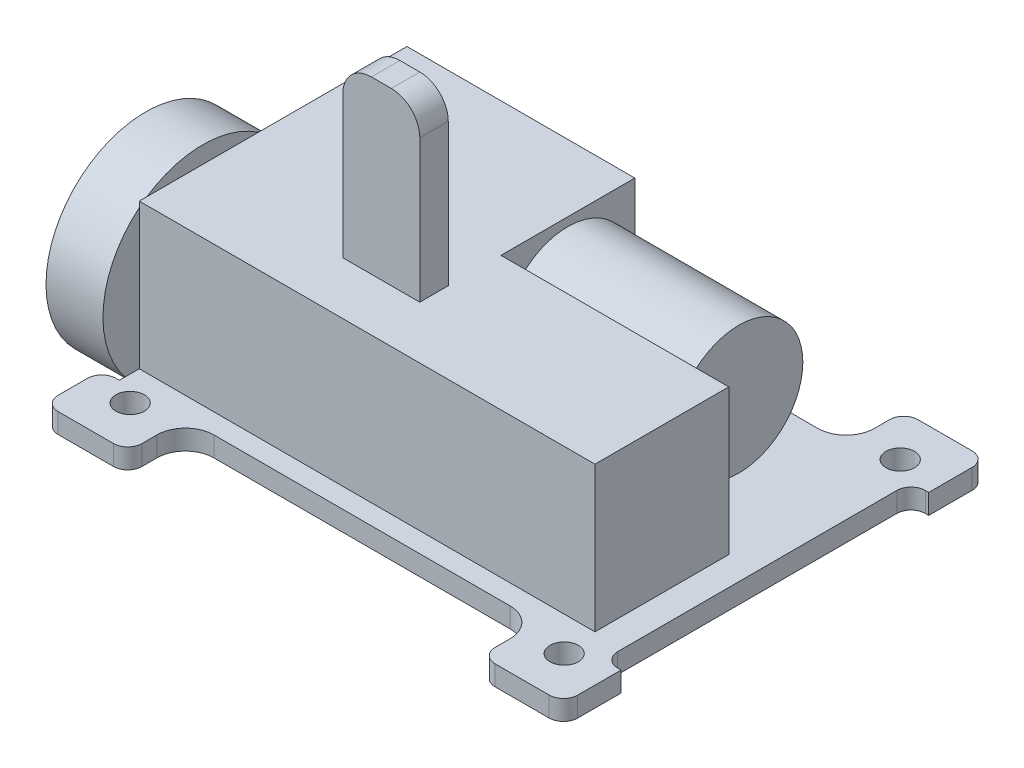
SolidWorks part; units mm, degrees
ref_plane "Front Plane" through (0, 0, 0) normal (0, 0, 1) x (1, 0, 0)
ref_plane "Top Plane" through (0, 0, 0) normal (0, 1, 0) x (1, 0, 0)
ref_plane "Right Plane" through (0, 0, 0) normal (1, 0, 0) x (0, 0, -1)
sketch "Sketch1" plane through (0, 0, 0) normal (0, 1, 0) x (1, 0, 0)
  line L0 (0, 0) -> (2.94, 0)
  line L1 (2.94, 0) -> (2.94, 2.025)
  line L2 (2.94, 2.025) -> (15.34, 2.025)
  line L3 (15.34, 2.025) -> (15.34, 0)
  line L4 (15.34, 0) -> (18.24, 0)
  line L5 (18.24, 0) -> (18.24, 2.025)
  line L6 (18.24, 2.025) -> (17.62, 2.025)
  line L7 (17.62, 2.025) -> (17.62, 12.825)
  line L8 (17.62, 12.825) -> (18.24, 12.825)
  line L9 (18.24, 12.825) -> (18.24, 14.85)
  line L10 (18.24, 14.85) -> (15.34, 14.85)
  line L11 (15.34, 14.85) -> (15.34, 12.825)
  line L12 (15.34, 12.825) -> (2.94, 12.825)
  line L13 (2.94, 12.825) -> (2.94, 14.85)
  line L14 (2.94, 14.85) -> (0, 14.85)
  line L15 (0, 14.85) -> (0, 12.825)
  line L16 (0, 12.825) -> (0.62, 12.825)
  line L17 (0.62, 12.825) -> (0.62, 2.025)
  line L18 (0.62, 2.025) -> (0, 2.025)
  line L19 (0, 2.025) -> (0, 0)
  circle A0 centre (1.5, 13.325) radius 0.5
  circle A1 centre (1.5, 1.525) radius 0.5
  circle A2 centre (16.74, 1.525) radius 0.5
  circle A3 centre (16.74, 13.325) radius 0.5
  dimension "D5" = 1
  dimension "D6" = 1.5
  dimension "D7" = 1.5
  dimension "D8" = 1.5
  dimension "D9" = 1.5
  dimension "D1" = 10.8
  dimension "D2" = 18.24
  dimension "D3" = 14.85
  dimension "D4" = 12.4
  dimension "D10" = 2.9
  dimension "D11" = 2.025
  dimension "D12" = 17
  dimension "D13" = 0.62
extrude "Boss-Extrude1" add sketch "Sketch1" along normal blind 0.7
fillet "Fillet1" radius 1 4 edges at (2.94, 0.35, -12.825) (15.34, 0.35, -12.825) (2.94, 0.35, -2.025) (15.34, 0.35, -2.025)
fillet "Fillet2" radius 0.5 12 edges at (0, 0.35, -2.025) (0, 0.35, 0) (2.94, 0.35, 0) (15.34, 0.35, 0) (18.24, 0.35, 0) (17.62, 0.35, -2.025) (17.62, 0.35, -12.825) (18.24, 0.35, -14.85) (15.34, 0.35, -14.85) (2.94, 0.35, -14.85) (0, 0.35, -14.85) (0.62, 0.35, -12.825)
sketch "Sketch2" plane through (0, 0.7, 0) normal (0, 1, 0) x (1, 0, 0)
  line L0 (0.62, 2.725) -> (16.62, 2.725)
  line L1 (16.62, 2.725) -> (16.62, 7.425)
  line L2 (16.62, 7.425) -> (8.62, 7.425)
  line L3 (8.62, 7.425) -> (8.62, 12.125)
  line L4 (8.62, 12.125) -> (0.62, 12.125)
  line L5 (0.62, 12.125) -> (0.62, 2.725)
  line L7 (9.14, 12.825) -> (9.14, 2.025) construction
  line L8 (14.34, 12.825) -> (3.94, 12.825) construction
  line L9 (3.94, 2.025) -> (14.34, 2.025) construction
  line L10 (0.62, 12.325) -> (0.62, 2.025) construction
  point P7 (0.62, 7.425)
  point P15 (9.14, 7.425)
  dimension "D1" = 9.4
  dimension "D2" = 16
  dimension "D3" = 8
extrude "Boss-Extrude2" add sketch "Sketch2" along normal blind 5.1
sketch "Sketch3" plane through (8.62, 0, 0) normal (1, 0, 0) x (0, 0, -1)
  line L0 (7.425, 0.7) -> (12.125, 5.8) construction
  line L1 (7.425, 5.8) -> (12.125, 0.7) construction
  circle A0 centre (9.775, 3.25) radius 2.25
  dimension "D1" = 4.5
extrude "Boss-Extrude7" add sketch "Sketch3" along normal blind 6
sketch "Sketch4" plane through (0, 0, 0) normal (0, -1, 0) x (1, 0, 0)
  line L0 (0.62, -7.175) -> (17.62, -7.175) construction
  line L1 (6.64, -4.675) -> (11.64, -4.675)
  line L2 (6.64, -4.675) -> (6.64, -9.675)
  line L3 (6.64, -9.675) -> (11.64, -9.675)
  line L4 (11.64, -4.675) -> (11.64, -9.675)
  line L7 (9.14, -2.025) -> (9.14, -12.825) construction
  line L8 (3.94, -2.025) -> (14.34, -2.025) construction
  line L9 (14.34, -12.825) -> (3.94, -12.825) construction
  line L10 (0.62, -12.325) -> (0.62, -2.025) construction
  line L11 (17.62, -2.525) -> (17.62, -12.325) construction
  point P16 (6.64, -7.175)
  point P17 (9.14, -4.675)
  dimension "D1" = 5
  dimension "D2" = 5
extrude "Boss-Extrude8" add sketch "Sketch4" along normal blind 1
sketch "Sketch5" plane through (0.62, 0, 0) normal (-1, 0, 0) x (0, 0, 1)
  line L0 (-7.175, 0) -> (-2.725, 5.8) construction
  line L2 (-7.175, 5.8) -> (-2.725, 0) construction
  line L4 (-12.325, 0) -> (-2.025, 0) construction
  line L6 (-2.725, 5.8) -> (-2.725, 0) construction
  line L7 (-12.125, 5.8) -> (-2.725, 5.8) construction
  circle A0 centre (-4.95, 2.9) radius 3.5
  dimension "D1" = 7
extrude "Boss-Extrude9" add sketch "Sketch5" along normal blind 2
sketch "Sketch6" plane through (0, 5.8, 0) normal (0, 1, 0) x (1, 0, 0)
  line L0 (8.62, 7.425) -> (8.62, 2.725) construction
  line L1 (5.92, 5.575) -> (8.62, 5.575)
  line L2 (5.92, 5.575) -> (5.92, 4.575)
  line L3 (5.92, 4.575) -> (8.62, 4.575)
  line L4 (8.62, 5.575) -> (8.62, 4.575)
  line L5 (0.62, 2.725) -> (16.62, 2.725) construction
  point P9 (8.62, 5.075)
  point P10 (8.62, 5.075)
  dimension "D1" = 1
  dimension "D2" = 2.7
extrude "Boss-Extrude10" add sketch "Sketch6" along normal blind 6
fillet "Fillet3" radius 1 2 edges at (5.92, 11.8, -5.075) (8.62, 11.8, -5.075)
